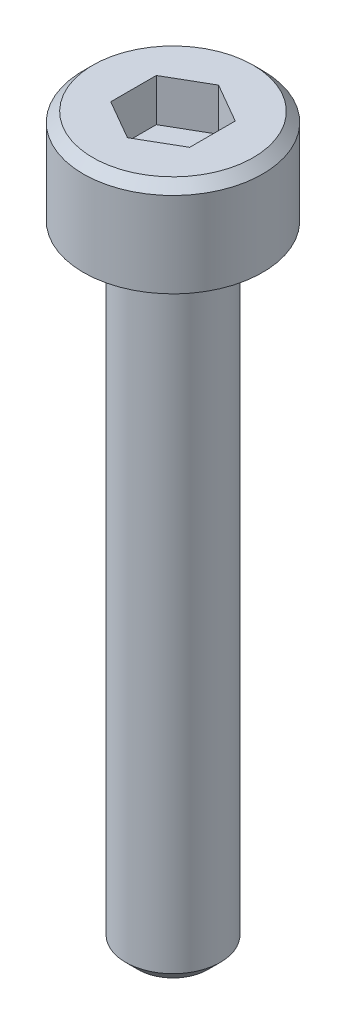
SolidWorks part; units mm, degrees
ref_plane "Front Plane" through (0, 0, 0) normal (0, 0, 1) x (1, 0, 0)
ref_plane "Top Plane" through (0, 0, 0) normal (0, 1, 0) x (1, 0, 0)
ref_plane "Right Plane" through (0, 0, 0) normal (1, 0, 0) x (0, 0, -1)
sketch "Sketch1" plane through (0, 0, 0) normal (0, 0, 1) x (1, 0, 0)
  line L0 (0, -20) -> (1.1, -20)
  line L1 (1.1, -20) -> (1.5, -19.6)
  line L2 (1.5, -19.6) -> (1.5, 0)
  line L3 (1.5, 0) -> (2.84, 0)
  line L4 (2.84, 0) -> (2.84, 2.7)
  line L5 (2.84, 2.7) -> (2.54, 3)
  line L6 (2.54, 3) -> (0, 3)
  line L7 (0, 3) -> (0, -20)
  line L8 (0, -10) -> (0, 1000) construction
revolve "Revolve1" add sketch "Sketch1" angle 360 about L8
cosmetic thread "Cosmetic Thread1" parameters "D1"=19.6, "D2"=2.4588
ref_plane "Plane1" through (0, 3, 0) normal (0, 1, 0) x (1, 0, 0)
sketch "Sketch2" plane through (0, 3, 0) normal (0, 1, 0) x (1, 0, 0)
  line L0 (1.25, -0.7217) -> (0, -1.4434)
  line L1 (0, -1.4434) -> (-1.25, -0.7217)
  line L2 (-1.25, -0.7217) -> (-1.25, 0.7217)
  line L3 (-1.25, 0.7217) -> (0, 1.4434)
  line L4 (0, 1.4434) -> (1.25, 0.7217)
  line L5 (1.25, 0.7217) -> (1.25, -0.7217)
extrude "Cut-Extrude1" cut sketch "Sketch2" against normal blind 1.35
